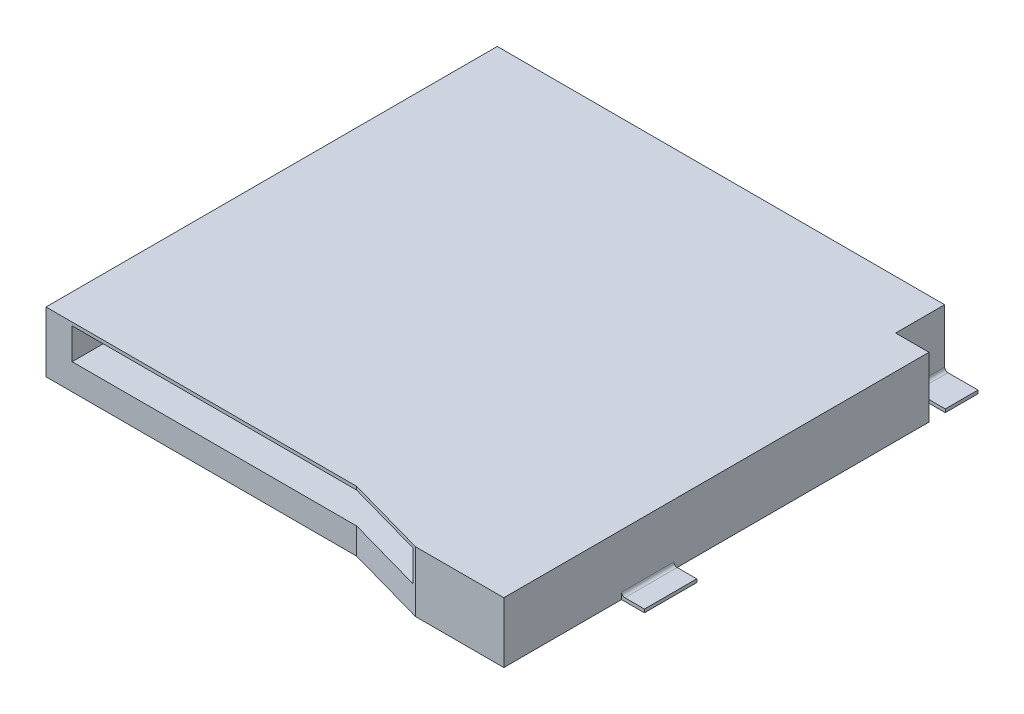
SolidWorks part; units mm, degrees
ref_plane "정면" through (0, 0, 0) normal (0, 0, 1) x (1, 0, 0)
ref_plane "윗면" through (0, 0, 0) normal (0, 1, 0) x (1, 0, 0)
ref_plane "우측면" through (0, 0, 0) normal (1, 0, 0) x (0, 0, -1)
sketch "스케치1" plane through (0, 0, 0) normal (0, 1, 0) x (1, 0, 0)
  line L0 (2.66, -6.15) -> (5.16, -6.85)
  line L1 (-6.84, 7.65) -> (6.84, 7.65)
  line L2 (-6.84, 7.65) -> (-6.84, -6.15)
  line L3 (-6.84, -6.15) -> (2.66, -6.15)
  line L4 (7.86, 6.15) -> (7.86, -6.85)
  line L5 (5.16, -6.85) -> (7.86, -6.85)
  line L6 (-6.84, -6.15) -> (6.84, 6.15) construction
  line L8 (6.84, 7.65) -> (6.84, 6.15)
  line L9 (6.84, 6.15) -> (7.86, 6.15)
  dimension "D1" = 14.7
  dimension "D2" = 0.7
  dimension "D3" = 14.5
  dimension "D4" = 2.7
  dimension "D5" = 9.5
  dimension "D6" = 1.02
  dimension "D7" = 1.5
extrude "보스-돌출1" add sketch "스케치1" along normal blind 1.85
sketch "스케치2" plane through (0, 0, 0) normal (0, 1, 0) x (1, 0, 0)
  line L0 (7.86, -6.85) -> (7.86, 6.15) construction
  line L1 (7.86, -1.65) -> (8.56, -1.65)
  line L2 (7.86, -1.65) -> (7.86, -3.25)
  line L3 (7.86, -3.25) -> (8.56, -3.25)
  line L4 (8.56, -1.65) -> (8.56, -3.25)
  line L5 (-6.84, 7.65) -> (-6.84, -6.15) construction
  line L6 (6.84, 6.15) -> (6.84, 7.65) construction
  line L7 (6.84, 7.65) -> (7.86, 7.65)
  line L8 (6.84, 7.65) -> (6.84, 6.65)
  line L9 (6.84, 6.65) -> (7.86, 6.65)
  line L10 (-6.84, 7.65) -> (-7.54, 7.65)
  line L11 (-6.84, 7.65) -> (-6.84, 6.65)
  line L12 (-6.84, 6.65) -> (-7.54, 6.65)
  line L13 (-7.54, 7.65) -> (-7.54, 6.65)
  line L14 (7.86, 7.65) -> (7.86, 6.65)
  line L15 (-6.84, -1.65) -> (-7.54, -1.65)
  line L16 (-6.84, -1.65) -> (-6.84, -3.25)
  line L17 (-6.84, -3.25) -> (-7.54, -3.25)
  line L18 (-7.54, -1.65) -> (-7.54, -3.25)
  line L19 (6.84, 7.65) -> (-6.84, 7.65) construction
  dimension "D1" = 1
  dimension "D2" = 1.02
  dimension "D3" = 1.6
  dimension "D4" = 0.7
  dimension "D5" = 1.6
  dimension "D6" = 0.7
  dimension "D7" = 1
  dimension "D8" = 0.7
  dimension "D9" = 9.3
extrude "보스-돌출2" add sketch "스케치2" along normal blind 0.1
sketch "스케치3" plane through (0, 0, 0) normal (0, -1, 0) x (1, 0, 0)
  line L0 (0, 6.9794) -> (0, -8.1783) construction
  line L1 (7.86, -7.65) -> (-7.54, -7.65) construction
  circle A0 centre (-4.95, 2.85) radius 0.4
  circle A1 centre (3.05, 2.85) radius 0.4
  dimension "D4" = 0.8
  dimension "D1" = 10.5
  dimension "D2" = 3.05
  dimension "D3" = 4.95
extrude "보스-돌출3" add sketch "스케치3" along normal blind 0.6
sketch "스케치4" plane through (0, 0, 0) normal (0, 0, 1) x (1, 0, 0)
  line L0 (-6.84, 1.85) -> (2.66, 1.85) construction
  line L1 (-6.04, 1.75) -> (5.06, 1.75)
  line L2 (-6.04, 1.75) -> (-6.04, 0.8)
  line L3 (-6.04, 0.8) -> (5.06, 0.8)
  line L4 (5.06, 1.75) -> (5.06, 0.8)
  line L6 (-6.84, 1.85) -> (-6.84, 0) construction
  line L7 (-6.84, 0) -> (2.66, 0) construction
  dimension "D1" = 0.1
  dimension "D2" = 11.1
  dimension "D3" = 0.8
  dimension "D4" = 0.8
extrude "컷-돌출1" cut sketch "스케치4" along normal through all and the other way blind 7
fillet "필렛1" radius 0.1 2 edges at (3.05, -0.6, 2.45) (-4.95, -0.6, 2.45)
fillet "필렛2" radius 0.1 4 edges at (6.84, 0.1, -7.15) (7.86, 0.1, 2.45) (-6.84, 0.1, 2.45)
sketch "스케치7" plane through (0, 0, 6.15) normal (0, 0, 1) x (1, 0, 0)
  line L0 (-6.84, 0) -> (2.66, 0) construction
  line L1 (-6.04, 1.75) -> (5.06, 1.75)
  line L2 (-6.04, 1.75) -> (-6.04, 0.8)
  line L3 (-6.04, 0.8) -> (5.06, 0.8)
  line L4 (5.06, 1.75) -> (5.06, 0.8)
  point P6 (-0.49, 0.8)
  point P7 (-0.49, 0)
